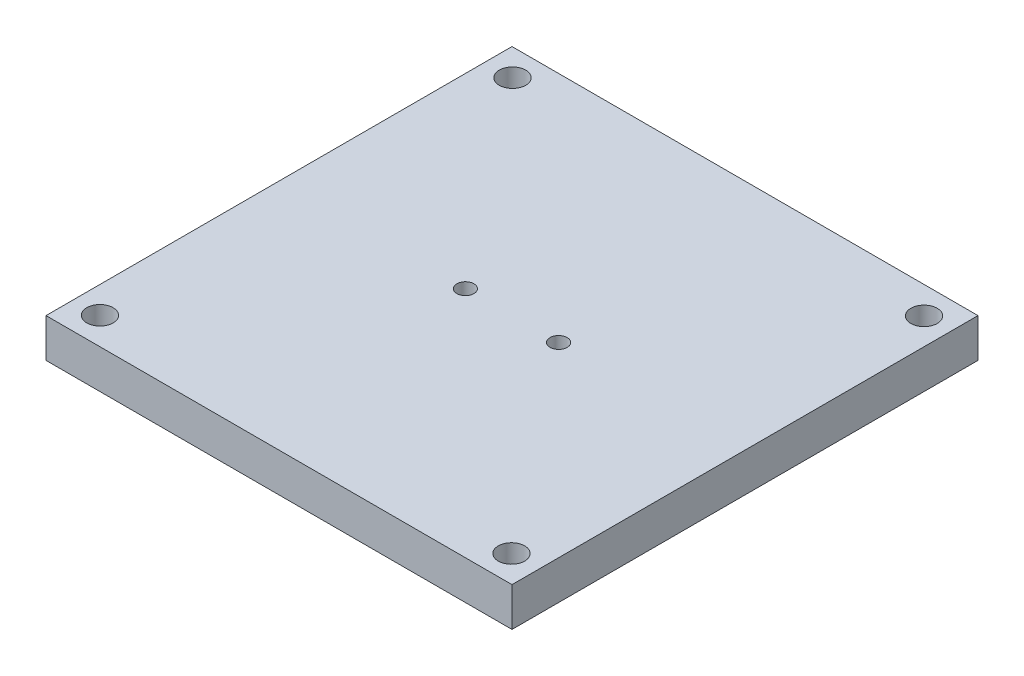
SolidWorks part; units mm, degrees
ref_plane "前视基准面" through (0, 0, 0) normal (0, 0, 1) x (1, 0, 0)
ref_plane "上视基准面" through (0, 0, 0) normal (0, 1, 0) x (1, 0, 0)
ref_plane "右视基准面" through (0, 0, 0) normal (1, 0, 0) x (0, 0, -1)
other "Configuration Table"
sketch "草图3" plane through (0, 0, 0) normal (0, 1, 0) x (1, 0, 0)
  line L0 (30, 60) -> (30, 30) construction
  line L1 (0, 0) -> (60, 0)
  line L2 (0, 0) -> (0, 60)
  line L3 (0, 60) -> (60, 60)
  line L4 (60, 0) -> (60, 60)
  circle A0 centre (36, 30) radius 1.1
  circle A1 centre (24, 30) radius 1.1
  circle A2 centre (3.5053, 56.5602) radius 1.7
  circle A3 centre (56.5602, 56.4947) radius 1.7
  circle A4 centre (56.4947, 3.4398) radius 1.7
  circle A5 centre (3.4398, 3.5053) radius 1.7
  point P22 (30, 30)
  dimension "D5" = 2.2
  dimension "D7" = 3.4
  dimension "D1" = 60
  dimension "D2" = 60
  dimension "D3" = 30
  dimension "D4" = 30
  dimension "D6" = 6
  dimension "D8" = 4
extrude "凸台-拉伸1" add sketch "草图3" along normal blind 5
